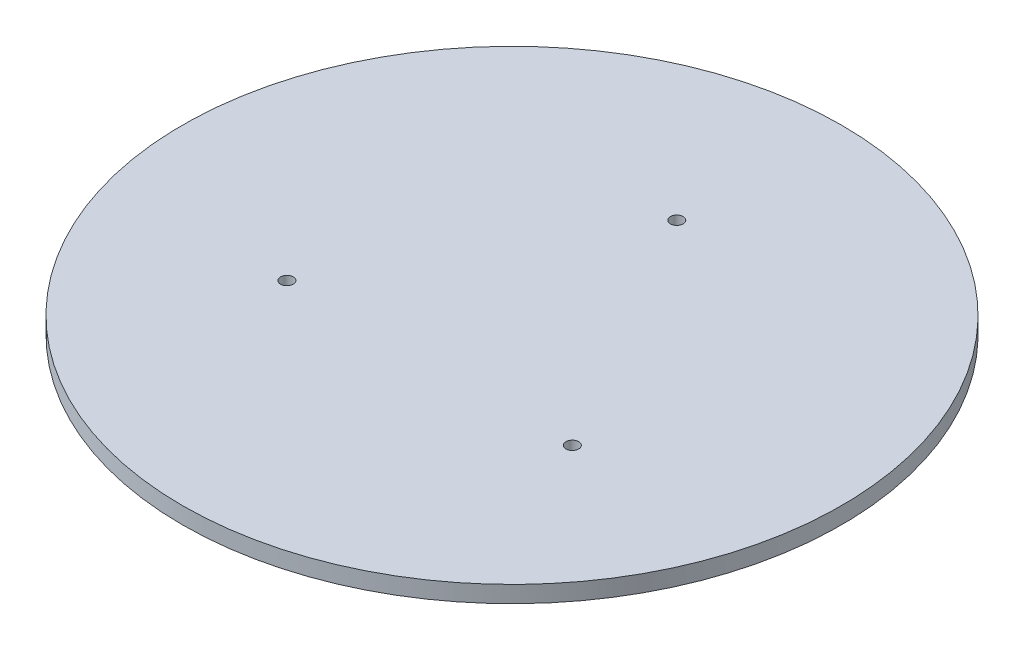
SolidWorks part; units mm, degrees
ref_plane "Front Plane" through (0, 0, 0) normal (0, 0, 1) x (1, 0, 0)
ref_plane "Top Plane" through (0, 0, 0) normal (0, 1, 0) x (1, 0, 0)
ref_plane "Right Plane" through (0, 0, 0) normal (1, 0, 0) x (0, 0, -1)
sketch "Sketch1" plane through (0, 0, 0) normal (0, 1, 0) x (1, 0, 0)
  line L0 (0, 0) -> (0, 125.3808) construction
  circle A0 centre (0, 0) radius 125.3808
  circle A1 centre (0, 62.6904) radius 2.4257
  circle A2 centre (54.2915, -31.3452) radius 2.4257
  circle A3 centre (-54.2915, -31.3452) radius 2.4257
  point P13 (0, 0)
  dimension "D1" = 250.7615
  dimension "D2" = 4.8514
  dimension "D3" = 3
extrude "Boss-Extrude1" add sketch "Sketch1" along normal blind 6.35
